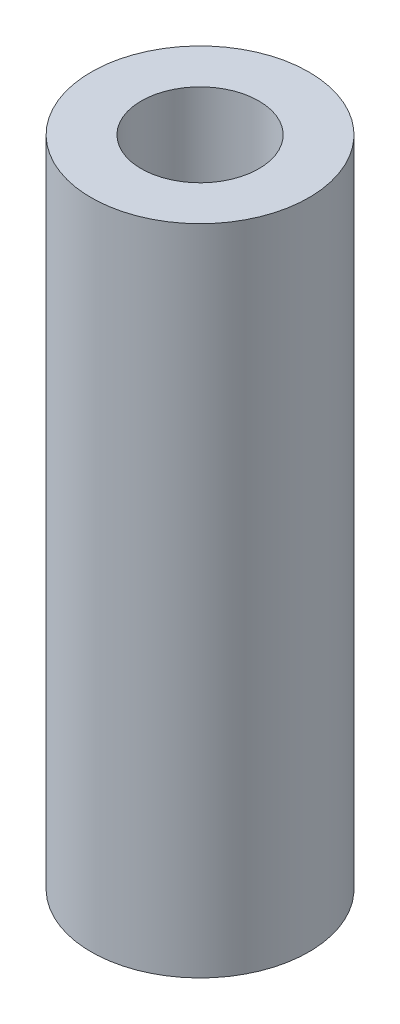
SolidWorks part; units mm, degrees
ref_plane "Front Plane" through (0, 0, 0) normal (0, 0, 1) x (1, 0, 0)
ref_plane "Top Plane" through (0, 0, 0) normal (0, 1, 0) x (1, 0, 0)
ref_plane "Right Plane" through (0, 0, 0) normal (1, 0, 0) x (0, 0, -1)
sketch "Sketch1" plane through (0, 0, 0) normal (0, 1, 0) x (1, 0, 0)
  circle A0 centre (0, 0) radius 3.429
  circle A1 centre (0, 0) radius 6.35
  dimension "D1" = 6.858
  dimension "D2" = 12.7
extrude "Boss-Extrude1" add sketch "Sketch1" along normal blind 38.1
